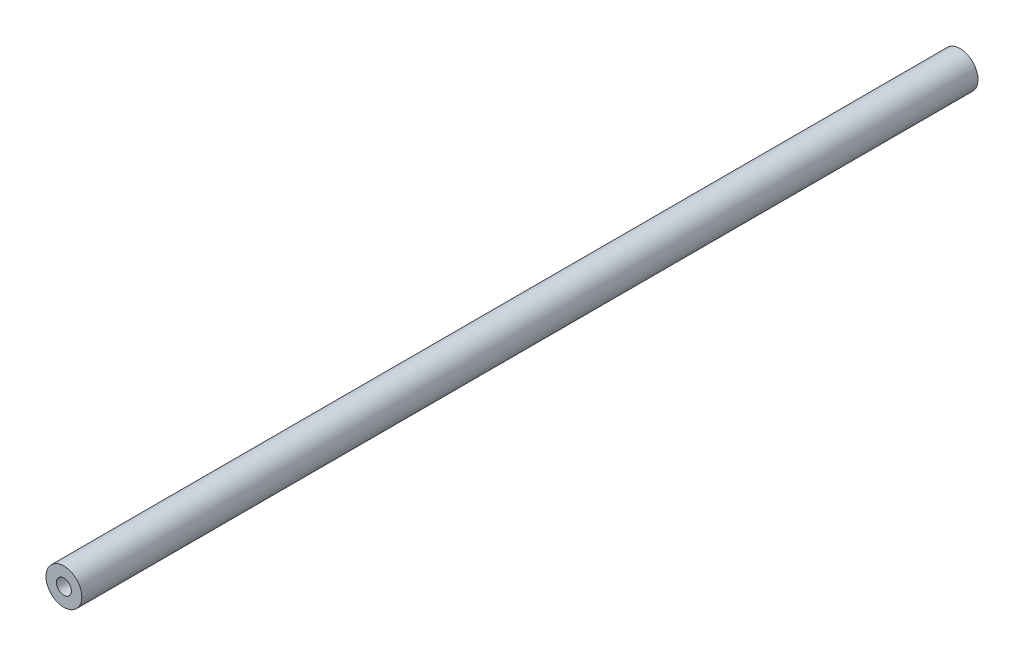
SolidWorks part; units mm, degrees
ref_plane "前视基准面" through (0, 0, 0) normal (0, 0, 1) x (1, 0, 0)
ref_plane "上视基准面" through (0, 0, 0) normal (0, 1, 0) x (1, 0, 0)
ref_plane "右视基准面" through (0, 0, 0) normal (1, 0, 0) x (0, 0, -1)
sketch "草图1" plane through (0, 0, 0) normal (0, 0, 1) x (1, 0, 0)
  circle A0 centre (0, 0) radius 6
  dimension "D1" = 12
extrude "凸台-拉伸1" add sketch "草图1" along normal mid plane 300
hole_wizard "M6 螺纹孔1" positions "草图3" profile "草图2" tap size "M6" standard "Iso"
sketch "草图3" plane through (0, 0, -150) normal (0, 0, -1) x (-1, 0, 0)
  point P0 (0, 0)
sketch "草图2" plane through (0, 0, -150) normal (1, 0, 0) x (0, 1, 0)
  line L0 (0, 0) -> (0, 16.5022)
  line L1 (0, 16.5022) -> (2.5, 15)
  line L2 (2.5, 15) -> (2.5, 0)
  line L5 (2.5, 0) -> (0, 0)
  line L10 (0, 16.5022) -> (-2.5, 15) construction
  line L11 (0, -6.35) -> (0, 107.95) construction
  dimension "螺纹孔钻头直径" = 5
  dimension "螺纹孔钻头深度" = 15
  dimension "导头角度" = 118
cosmetic thread "孔螺蚊线1" parameters "D1"=12, "D2"=6
hole_wizard "M6 螺纹孔2" positions "草图5" profile "草图6" tap size "M6" standard "ISO"
sketch "草图5" plane through (0, 0, 150) normal (0, 0, 1) x (1, 0, 0)
  point P0 (0, 0)
sketch "草图6" plane through (0, 0, 150) normal (1, 0, 0) x (0, -1, 0)
  line L0 (0, 0) -> (0, 16.5022)
  line L1 (0, 16.5022) -> (2.5, 15)
  line L2 (2.5, 15) -> (2.5, 0)
  line L5 (2.5, 0) -> (0, 0)
  line L10 (0, 16.5022) -> (-2.5, 15) construction
  line L11 (0, -6.35) -> (0, 107.95) construction
  dimension "螺纹孔钻头直径" = 5
  dimension "螺纹孔钻头深度" = 15
  dimension "导头角度" = 118
cosmetic thread "孔螺蚊线2" parameters "D1"=12, "D2"=6
